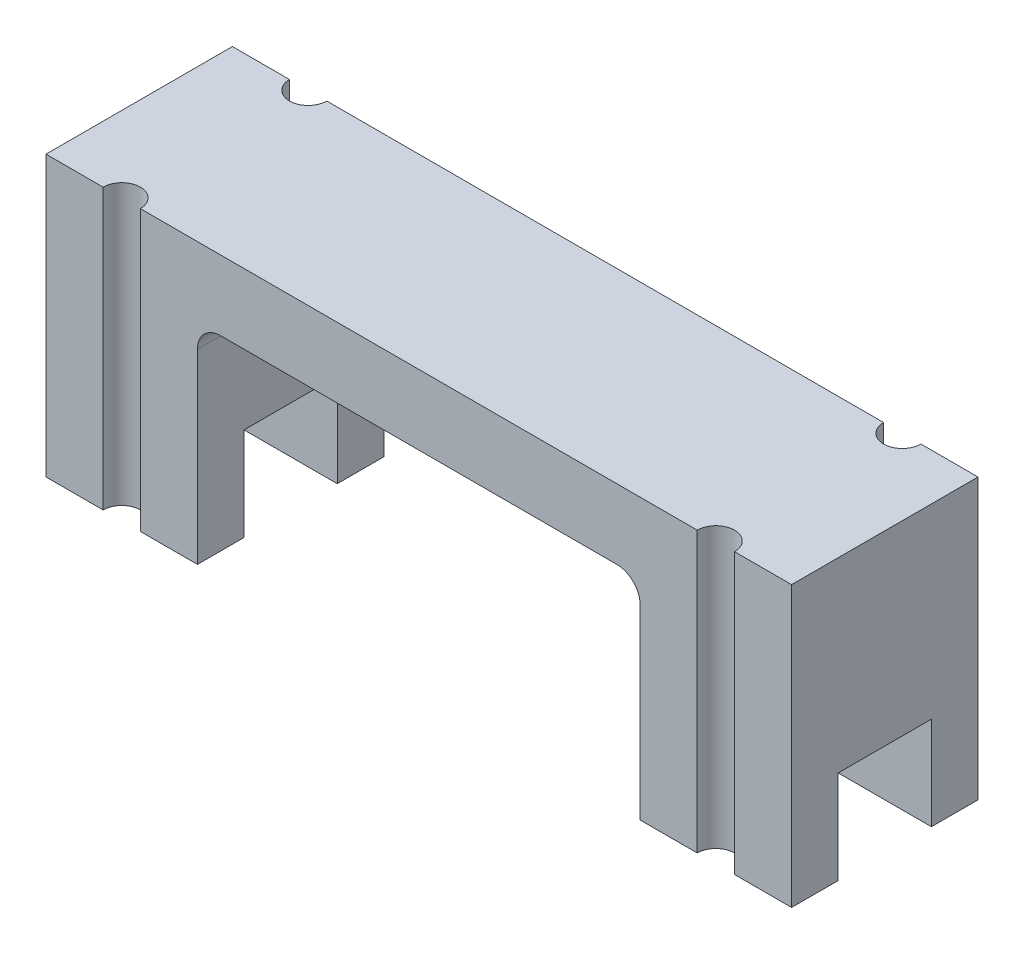
SolidWorks part; units mm, degrees
ref_plane "前视基准面" through (0, 0, 0) normal (0, 0, 1) x (1, 0, 0)
ref_plane "上视基准面" through (0, 0, 0) normal (0, 1, 0) x (1, 0, 0)
ref_plane "右视基准面" through (0, 0, 0) normal (1, 0, 0) x (0, 0, -1)
sketch "草图1" plane through (0, 0, 0) normal (0, 0, 1) x (1, 0, 0)
  line L1 (-80, 30) -> (80, 30)
  line L2 (-80, 30) -> (-80, -30)
  line L3 (-80, -30) -> (80, -30)
  line L4 (80, 30) -> (80, -30)
  line L5 (-80, 30) -> (80, -30) construction
  line L6 (-80, -30) -> (80, 30) construction
  point P0 (0, 0)
  dimension "D1" = 160
  dimension "D2" = 60
extrude "凸台-拉伸1" add sketch "草图1" along normal blind 30
sketch "草图2" plane through (-80, 0, 0) normal (-1, 0, 0) x (0, 0, 1)
  line L0 (30, -30) -> (0, -30) construction
  line L1 (25, -50) -> (5, -50)
  line L2 (25, -50) -> (25, -10)
  line L3 (25, -10) -> (5, -10)
  line L4 (5, -50) -> (5, -10)
  line L5 (25, -50) -> (5, -10) construction
  line L6 (25, -10) -> (5, -50) construction
  point P0 (15, -30)
  dimension "D1" = 20
  dimension "D2" = 20
extrude "切除-拉伸1" cut sketch "草图2" against normal blind 171
sketch "草图3" plane through (0, 0, 30) normal (0, 0, 1) x (1, 0, 0)
  line L0 (-80, -30) -> (80, -30) construction
  line L1 (47.5, -75) -> (-47.5, -75)
  line L2 (47.5, -75) -> (47.5, 15)
  line L3 (47.5, 15) -> (-47.5, 15)
  line L4 (-47.5, -75) -> (-47.5, 15)
  line L5 (47.5, -75) -> (-47.5, 15) construction
  line L6 (47.5, 15) -> (-47.5, -75) construction
  line L7 (80, 30) -> (-80, 30) construction
  point P0 (0, -30)
  dimension "D1" = 95
  dimension "D2" = 15
extrude "切除-拉伸2" cut sketch "草图3" against normal blind 171
fillet "圆角1" radius 5 2 edges at (47.5, 15, 15) (-47.5, 15, 15)
sketch "草图4" plane through (0, 0, 30) normal (0, 0, 1) x (1, 0, 0)
  line L8 (-47.5, -30) -> (-47.5, 10)
  line L9 (-42.5, 15) -> (42.5, 15)
  line L10 (47.5, 10) -> (47.5, -30)
  line L11 (47.5, -30) -> (80, -30)
  line L12 (80, -30) -> (80, 30)
  line L13 (80, 30) -> (-80, 30)
  line L14 (-80, 30) -> (-80, -30)
  line L15 (-80, -30) -> (-47.5, -30)
  line L16 (-47.5, -30) -> (-47.5, 10)
  line L17 (-42.5, 15) -> (42.5, 15)
  line L18 (47.5, 10) -> (47.5, -30)
  line L19 (47.5, -30) -> (80, -30)
  line L20 (80, -30) -> (80, 30)
  line L21 (80, 30) -> (-80, 30)
  line L22 (-80, 30) -> (-80, -30)
  line L23 (-80, -30) -> (-47.5, -30)
  arc A2 (-42.5, 15) -> (-47.5, 10) centre (-42.5, 10) ccw
  arc A3 (47.5, 10) -> (42.5, 15) centre (42.5, 10) ccw
  arc A4 (-42.5, 15) -> (-47.5, 10) centre (-42.5, 10) ccw
  arc A5 (47.5, 10) -> (42.5, 15) centre (42.5, 10) ccw
  dimension "D1" = 0
extrude "凸台-拉伸2" add sketch "草图4" along normal blind 5
sketch "草图5" plane through (0, 0, 0) normal (0, 0, -1) x (-1, 0, 0)
  line L8 (-47.5, -30) -> (-47.5, 10)
  line L9 (-42.5, 15) -> (42.5, 15)
  line L10 (47.5, 10) -> (47.5, -30)
  line L11 (47.5, -30) -> (80, -30)
  line L12 (80, -30) -> (80, 30)
  line L13 (80, 30) -> (-80, 30)
  line L14 (-80, 30) -> (-80, -30)
  line L15 (-80, -30) -> (-47.5, -30)
  line L16 (-47.5, -30) -> (-47.5, 10)
  line L17 (-42.5, 15) -> (42.5, 15)
  line L18 (47.5, 10) -> (47.5, -30)
  line L19 (47.5, -30) -> (80, -30)
  line L20 (80, -30) -> (80, 30)
  line L21 (80, 30) -> (-80, 30)
  line L22 (-80, 30) -> (-80, -30)
  line L23 (-80, -30) -> (-47.5, -30)
  arc A2 (-42.5, 15) -> (-47.5, 10) centre (-42.5, 10) ccw
  arc A3 (47.5, 10) -> (42.5, 15) centre (42.5, 10) ccw
  arc A4 (-42.5, 15) -> (-47.5, 10) centre (-42.5, 10) ccw
  arc A5 (47.5, 10) -> (42.5, 15) centre (42.5, 10) ccw
  dimension "D1" = 0
extrude "凸台-拉伸3" add sketch "草图5" along normal blind 5
sketch "草图6" plane through (0, 15, 0) normal (0, -1, 0) x (1, 0, 0)
  line L0 (-80, 35) -> (-47.5, 35) construction
  line L1 (-47.5, -5) -> (-80, -5) construction
  line L2 (80, -5) -> (47.5, -5) construction
  line L3 (47.5, 35) -> (80, 35) construction
  circle A0 centre (-63.75, 35) radius 4
  circle A1 centre (-63.75, -5) radius 4
  circle A2 centre (63.75, -5) radius 4
  circle A3 centre (63.75, 35) radius 4
  dimension "D1" = 8
extrude "切除-拉伸3" cut sketch "草图6" against normal blind 33 and the other way blind 91
